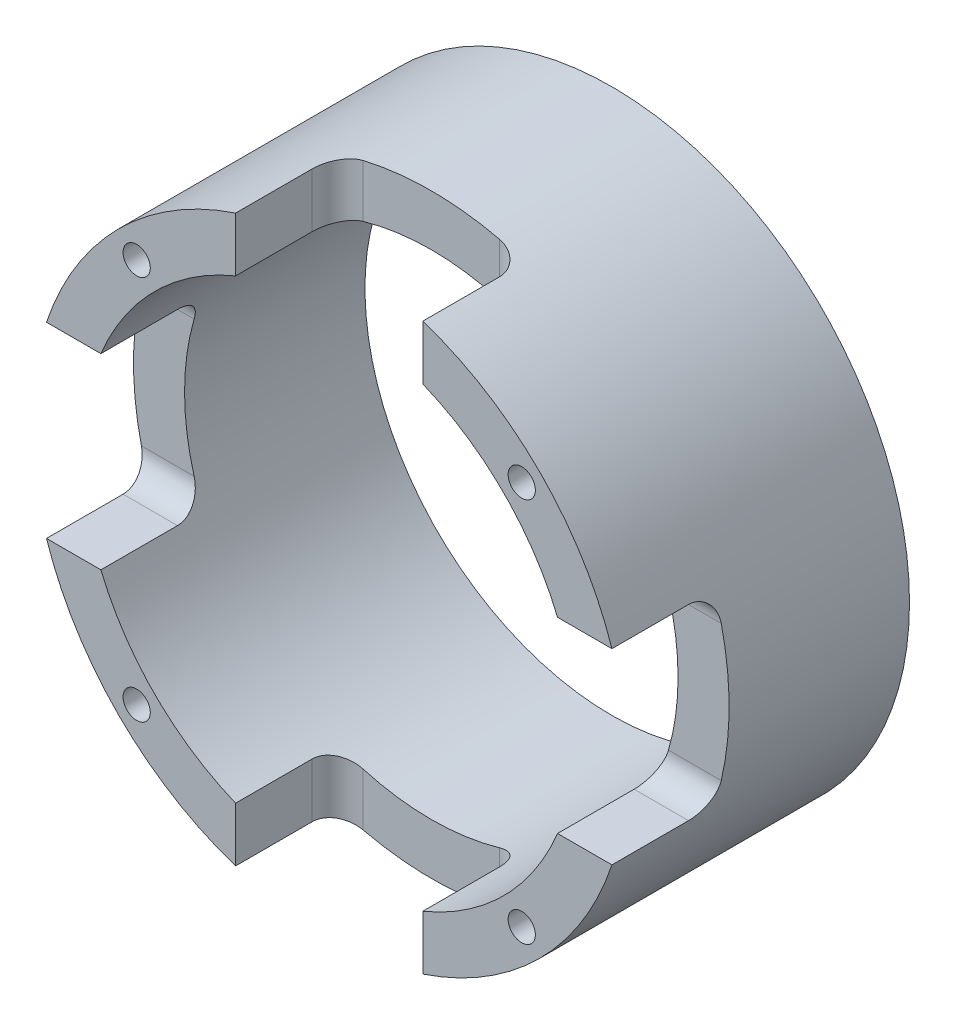
SolidWorks part; units mm, degrees
ref_plane "前视基准面" through (0, 0, 0) normal (0, 0, 1) x (1, 0, 0)
ref_plane "上视基准面" through (0, 0, 0) normal (0, 1, 0) x (1, 0, 0)
ref_plane "右视基准面" through (0, 0, 0) normal (1, 0, 0) x (0, 0, -1)
sketch "草图1" plane through (0, 0, 0) normal (0, 0, 1) x (1, 0, 0)
  line L0 (0, 0) -> (0, 14.5134) construction
  line L1 (0, 0) -> (-31.5369, 31.5369) construction
  circle A0 centre (0, 0) radius 29
  circle A1 centre (0, 0) radius 35
  circle A2 centre (0, 0) radius 32 construction
  circle A3 centre (-22.6274, 22.6274) radius 1.6
  circle A4 centre (22.6274, 22.6274) radius 1.6
  circle A5 centre (22.6274, -22.6274) radius 1.6
  circle A6 centre (-22.6274, -22.6274) radius 1.6
  point P18 (0, 0)
  dimension "D1" = 58
  dimension "D2" = 70
  dimension "D4" = 64
  dimension "D5" = 3.2
  dimension "D3" = 45
  dimension "D6" = 4
extrude "凸台-拉伸1" add sketch "草图1" along normal blind 33.2
sketch "草图3" plane through (0, 0, 33.2) normal (0, 0, 1) x (1, 0, 0)
  line L0 (-11, 21.3387) -> (-11, 44.4284)
  line L1 (11, 44.4284) -> (11, 21.3387)
  line L2 (-11, 44.4284) -> (11, 44.4284)
  line L3 (-11, 21.3387) -> (11, 21.3387)
  line L4 (21.3387, 11) -> (44.4284, 11)
  line L5 (44.4284, -11) -> (21.3387, -11)
  line L6 (44.4284, 11) -> (44.4284, -11)
  line L7 (21.3387, 11) -> (21.3387, -11)
  line L8 (11, -21.3387) -> (11, -44.4284)
  line L9 (-11, -44.4284) -> (-11, -21.3387)
  line L10 (11, -44.4284) -> (-11, -44.4284)
  line L11 (11, -21.3387) -> (-11, -21.3387)
  line L12 (-21.3387, -11) -> (-44.4284, -11)
  line L13 (-44.4284, 11) -> (-21.3387, 11)
  line L14 (-44.4284, -11) -> (-44.4284, 11)
  line L15 (-21.3387, -11) -> (-21.3387, 11)
  point P20 (0, 0)
  dimension "D1" = 11
  dimension "D2" = 11
  dimension "D3" = 4
extrude "切除-拉伸1" cut sketch "草图3" against normal blind 12
fillet "圆角1" radius 3 8 edges at (30.0297, 11, 21.2) (30.0297, -11, 21.2) (11, -30.0297, 21.2) (-11, -30.0297, 21.2) (-30.0297, 11, 21.2) (-30.0297, -11, 21.2) (11, 30.0297, 21.2) (-11, 30.0297, 21.2)
